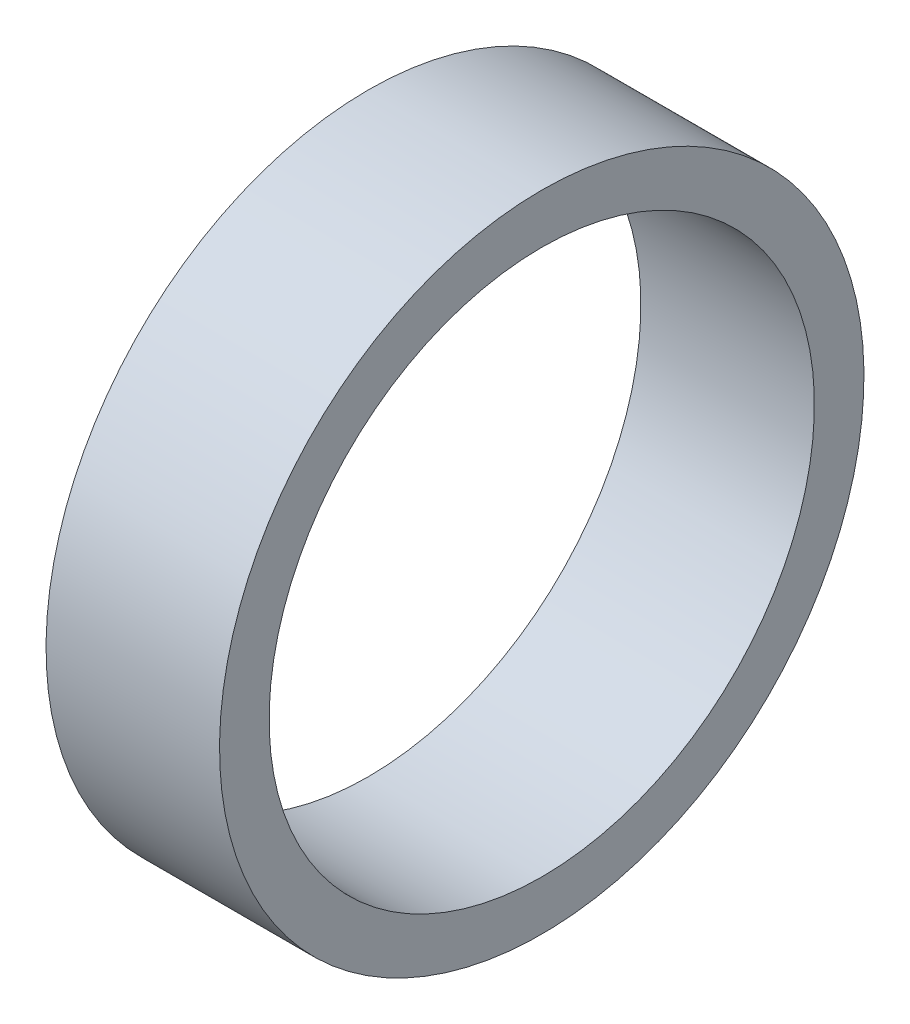
SolidWorks part; units mm, degrees
material "5052-H32"
ref_plane "Front Plane" through (0, 0, 0) normal (0, 0, 1) x (1, 0, 0)
ref_plane "Top Plane" through (0, 0, 0) normal (0, 1, 0) x (1, 0, 0)
ref_plane "Right Plane" through (0, 0, 0) normal (1, 0, 0) x (0, 0, -1)
sketch "Sketch2" plane through (0, 0, 0) normal (0, 0, 1) x (1, 0, 0)
  line L0 (0, 0) -> (0, 11) construction
  line L1 (0, 11) -> (0, 13)
  line L2 (0, 13) -> (-7, 13)
  line L3 (-7, 13) -> (-7, 11)
  line L4 (0, 11) -> (-7, 11)
  line L6 (0, 0) -> (-7, 0) construction
  line L7 (-7, 0) -> (-7, 11) construction
  point P4 (-8.0019, 11)
  point P7 (-7.8718, 11)
  dimension "D1" = 13
  dimension "D2" = 11
  dimension "D3" = 7
revolve "Revolve1" add sketch "Sketch2" angle 360 about L6
